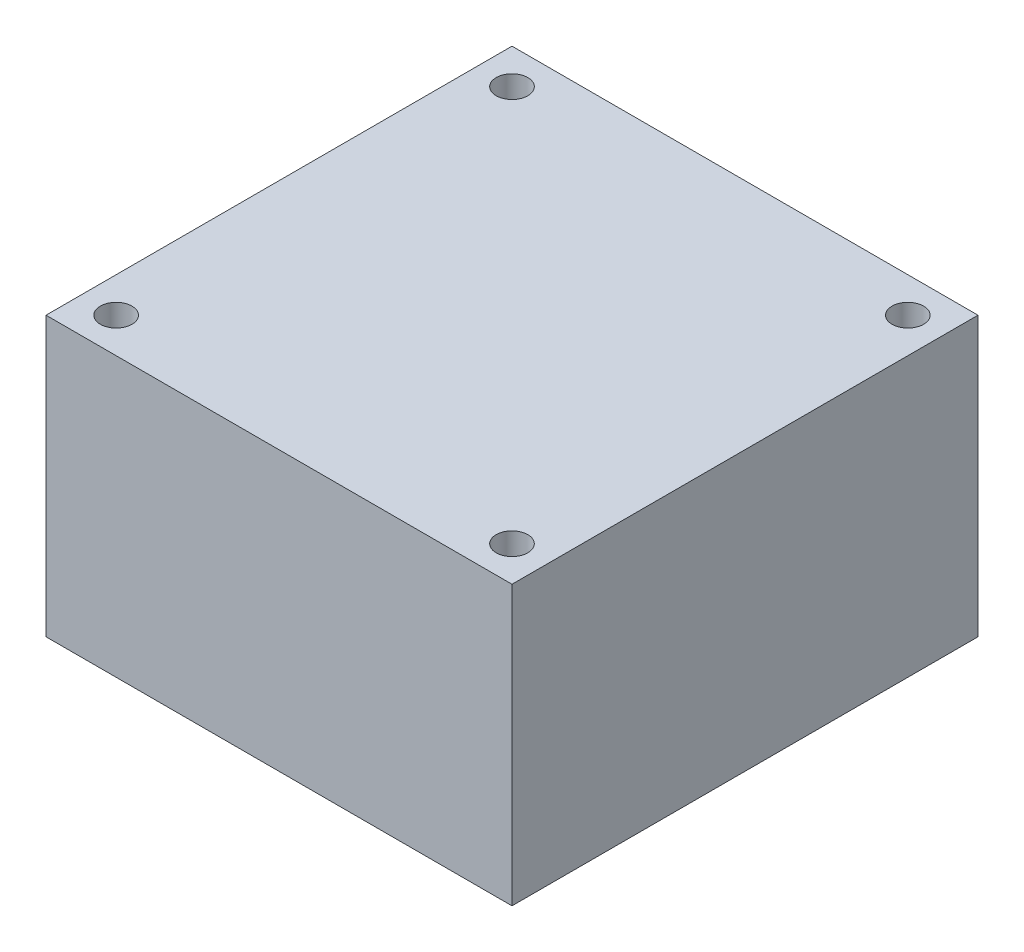
SolidWorks part; units mm, degrees
ref_plane "Front Plane" through (0, 0, 0) normal (0, 0, 1) x (1, 0, 0)
ref_plane "Top Plane" through (0, 0, 0) normal (0, 1, 0) x (1, 0, 0)
ref_plane "Right Plane" through (0, 0, 0) normal (1, 0, 0) x (0, 0, -1)
sketch "Sketch1" plane through (0, 0, 0) normal (0, 1, 0) x (1, 0, 0)
  line L1 (-21.75, 21.75) -> (21.75, 21.75)
  line L2 (-21.75, 21.75) -> (-21.75, -21.75)
  line L3 (-21.75, -21.75) -> (21.75, -21.75)
  line L4 (21.75, 21.75) -> (21.75, -21.75)
  line L5 (-21.75, 21.75) -> (21.75, -21.75) construction
  line L6 (-21.75, -21.75) -> (21.75, 21.75) construction
  point P0 (0, 0)
  dimension "D1" = 43.5
  dimension "D2" = 43.5
extrude "Boss-Extrude1" add sketch "Sketch1" along normal blind 26
sketch "Sketch2" plane through (0, 26, 0) normal (0, 1, 0) x (1, 0, 0)
  line L1 (-18.475, 18.475) -> (18.475, 18.475) construction
  line L2 (-18.475, 18.475) -> (-18.475, -18.475) construction
  line L3 (-18.475, -18.475) -> (18.475, -18.475) construction
  line L4 (18.475, 18.475) -> (18.475, -18.475) construction
  line L5 (-18.475, 18.475) -> (18.475, -18.475) construction
  line L6 (-18.475, -18.475) -> (18.475, 18.475) construction
  circle A0 centre (-18.475, 18.475) radius 1.475
  circle A1 centre (-18.475, -18.475) radius 1.475
  circle A2 centre (18.475, -18.475) radius 1.475
  circle A3 centre (18.475, 18.475) radius 1.475
  point P0 (0, 0)
  dimension "D1" = 2.95
  dimension "D2" = 36.95
extrude "Cut-Extrude1" cut sketch "Sketch2" against normal through all
